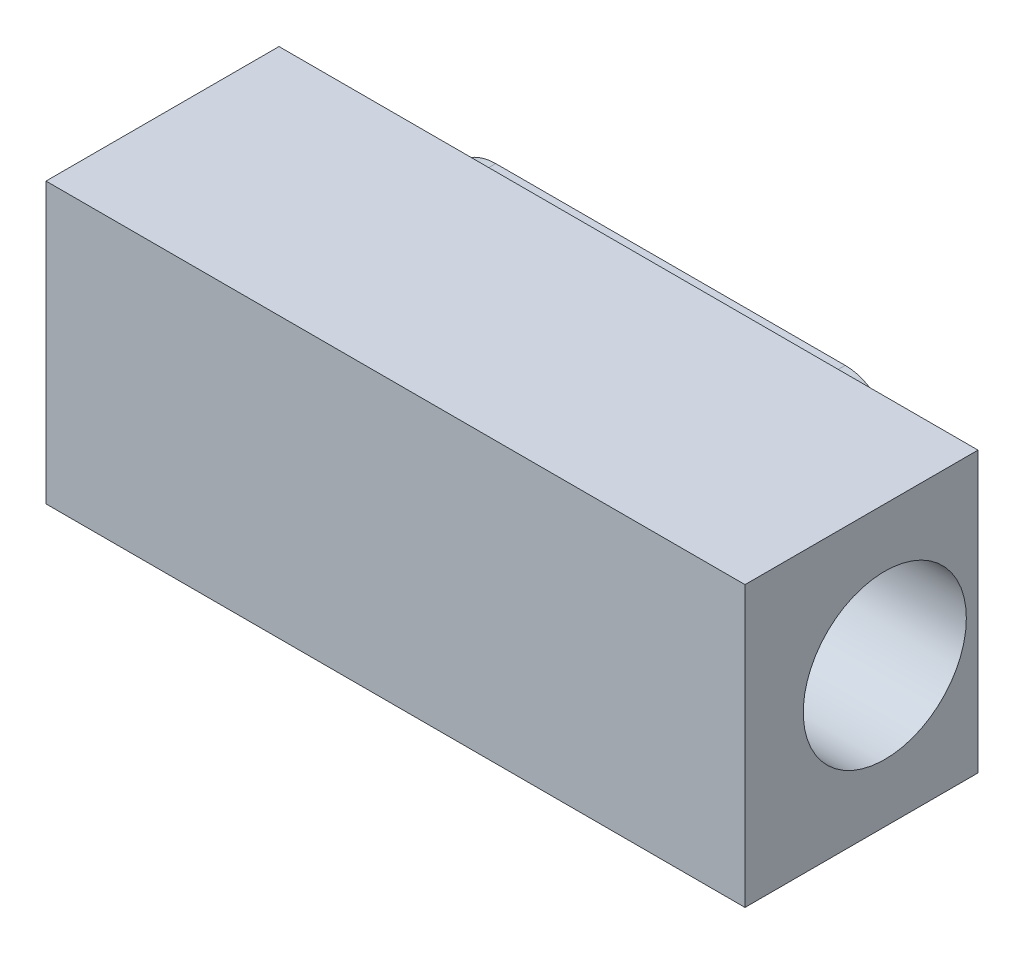
SolidWorks part; units mm, degrees
ref_plane "Přední rovina" through (0, 0, 0) normal (0, 0, 1) x (1, 0, 0)
ref_plane "Horní rovina" through (0, 0, 0) normal (0, 1, 0) x (1, 0, 0)
ref_plane "Pravá rovina" through (0, 0, 0) normal (1, 0, 0) x (0, 0, -1)
sketch "Skica1" plane through (0, 0, 0) normal (0, 0, 1) x (1, 0, 0)
  line L1 (-7.5, 4.5) -> (7.5, 4.5)
  line L2 (-9.5, 2.5) -> (-9.5, -2.5)
  line L3 (-7.5, -4.5) -> (7.5, -4.5)
  line L4 (9.5, 2.5) -> (9.5, -2.5)
  line L5 (-9.5, 4.5) -> (9.5, -4.5) construction
  line L6 (-9.5, -4.5) -> (9.5, 4.5) construction
  arc A0 (7.5, -4.5) -> (9.5, -2.5) centre (7.5, -2.5) ccw
  arc A1 (7.5, 4.5) -> (9.5, 2.5) centre (7.5, 2.5) cw
  arc A2 (-7.5, 4.5) -> (-9.5, 2.5) centre (-7.5, 2.5) ccw
  arc A3 (-9.5, -2.5) -> (-7.5, -4.5) centre (-7.5, -2.5) ccw
  point P0 (0, 0)
  dimension "D3" = 2
  dimension "D1" = 19
  dimension "D2" = 9
extrude "Přidat vysunutím1" add sketch "Skica1" along normal blind 1.8
sketch "Skica2" plane through (0, 0, 1.8) normal (0, 0, 1) x (1, 0, 0)
  line L1 (-15, 6) -> (15, 6)
  line L2 (-15, 6) -> (-15, -6)
  line L3 (-15, -6) -> (15, -6)
  line L4 (15, 6) -> (15, -6)
  line L5 (-15, 6) -> (15, -6) construction
  line L6 (-15, -6) -> (15, 6) construction
  point P0 (0, 0)
  dimension "D1" = 12
  dimension "D2" = 30
extrude "Přidat vysunutím2" add sketch "Skica2" along normal blind 10
sketch "Skica3" plane through (15, 0, 0) normal (1, 0, 0) x (0, 0, -1)
  circle A0 centre (-5.8, 0) radius 3.5
  dimension "D1" = 7
  dimension "D2" = 4
extrude "Odebrat vysunutím1" cut sketch "Skica3" against normal blind 20
sketch "Skica4" plane through (0, 0, 1.8) normal (0, 0, -1) x (-1, 0, 0)
  line L1 (8, -3) -> (-8, -3)
  line L2 (8, -3) -> (8, 3)
  line L3 (8, 3) -> (-8, 3)
  line L4 (-8, -3) -> (-8, 3)
  line L5 (8, -3) -> (-8, 3) construction
  line L6 (8, 3) -> (-8, -3) construction
  point P0 (0, 0)
  dimension "D1" = 16
  dimension "D2" = 6
extrude "Odebrat vysunutím2" cut sketch "Skica4" against normal blind 1.5 and the other way blind 1
